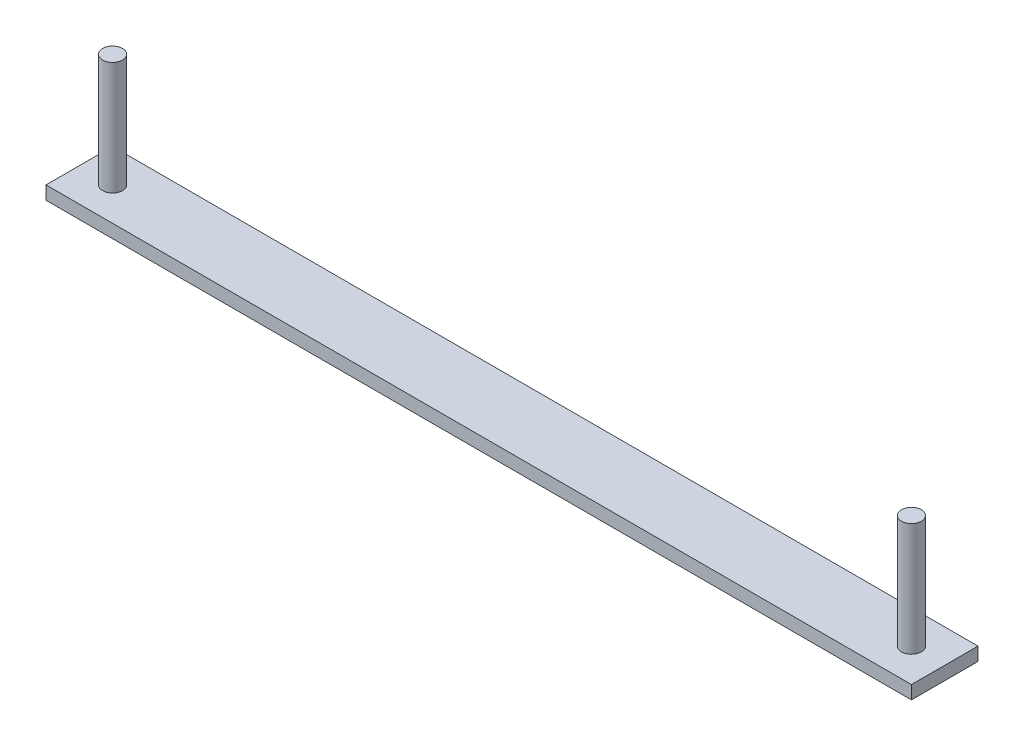
SolidWorks part; units mm, degrees
ref_plane "Front Plane" through (0, 0, 0) normal (0, 0, 1) x (1, 0, 0)
ref_plane "Top Plane" through (0, 0, 0) normal (0, 1, 0) x (1, 0, 0)
ref_plane "Right Plane" through (0, 0, 0) normal (1, 0, 0) x (0, 0, -1)
sketch "Sketch3" plane through (0, 0, 0) normal (0, 1, 0) x (1, 0, 0)
  line L0 (-55, 0) -> (55, 0) construction
  line L1 (-65, -5) -> (65, -5)
  line L2 (-65, -5) -> (-65, 5)
  line L3 (-65, 5) -> (65, 5)
  line L4 (65, -5) -> (65, 5)
  line L5 (-65, -5) -> (65, 5) construction
  line L6 (-65, 5) -> (65, -5) construction
  line L7 (0, 0) -> (0, 16.9167) construction
  point P0 (0, 0)
  dimension "D1" = 10
  dimension "D2" = 130
extrude "Boss-Extrude1" add sketch "Sketch3" along normal blind 2
sketch "Sketch4" plane through (0, 2, 0) normal (0, 1, 0) x (1, 0, 0)
  line L0 (-65, 5) -> (-65, -5) construction
  circle A0 centre (-60, 0) radius 1.5
  point P2 (0, 0)
  dimension "D2" = 3
  dimension "D1" = 5
extrude "Boss-Extrude2" add sketch "Sketch4" along normal blind 17
ref_plane "Plane1" through (0, 0, 0) normal (-1, 0, 0) x (0, 0, 1)
mirror "Mirror1" about plane through (0, 0, 0) normal (-1, 0, 0) of "Boss-Extrude2"
